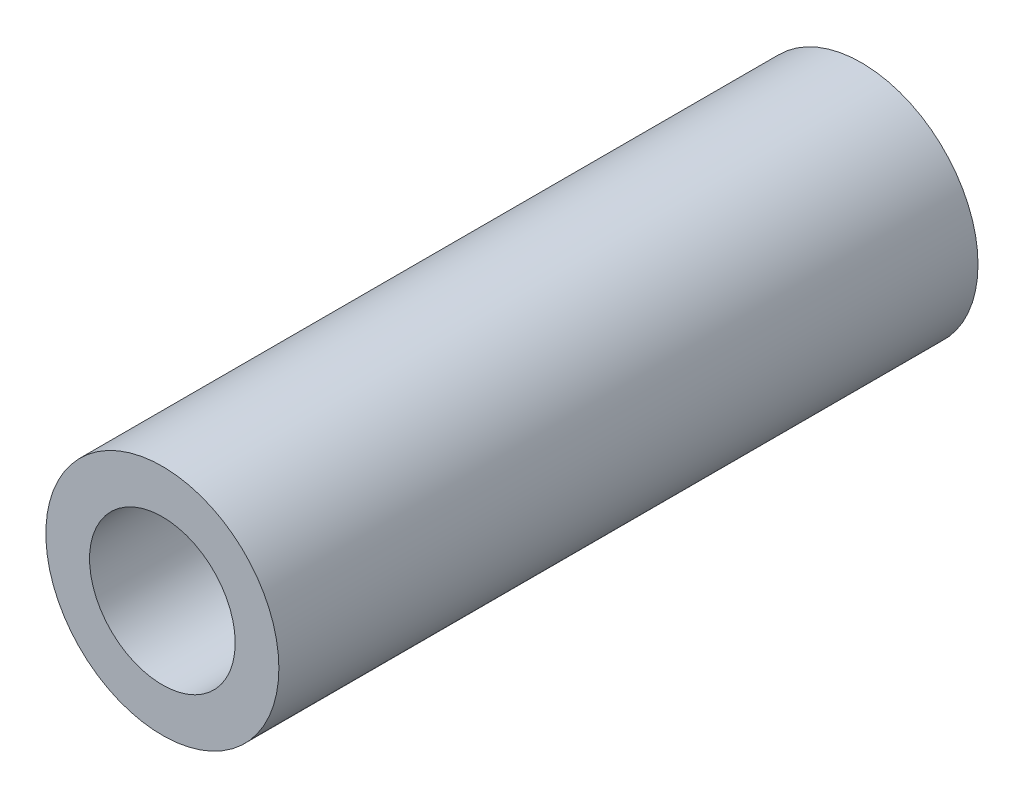
SolidWorks part; units mm, degrees
ref_plane "Plan de face" through (0, 0, 0) normal (0, 0, 1) x (1, 0, 0)
ref_plane "Plan de dessus" through (0, 0, 0) normal (0, 1, 0) x (1, 0, 0)
ref_plane "Plan de droite" through (0, 0, 0) normal (1, 0, 0) x (0, 0, -1)
sketch "Esquisse1" plane through (0, 0, 0) normal (0, 0, 1) x (1, 0, 0)
  circle A0 centre (0, 0) radius 2
extrude "Boss.-Extru.1" add sketch "Esquisse1" along normal blind 12
hole_wizard "Trou taraudé M31" positions "Esquisse4" profile "Esquisse3" tap size "M3" standard "ISO" end condition through all
sketch "Esquisse4" plane through (0, 0, 12) normal (0, 0, 1) x (1, 0, 0)
  point P0 (0, 0)
sketch "Esquisse3" plane through (0, 0, 12) normal (1, 0, 0) x (0, -1, 0)
  line L0 (0, 0) -> (0, 12)
  line L1 (0, 12) -> (1.25, 12)
  line L2 (1.25, 12) -> (1.25, 0)
  line L5 (1.25, 0) -> (0, 0)
  line L11 (0, -6.35) -> (0, 107.95) construction
  dimension "Diamètre du trou pour taraudage jusqu'au prochain" = 2.5
  dimension "Profondeur du trou pour taraudage jusqu'au prochain" = 12
cosmetic thread "Filetage de perçage1"
